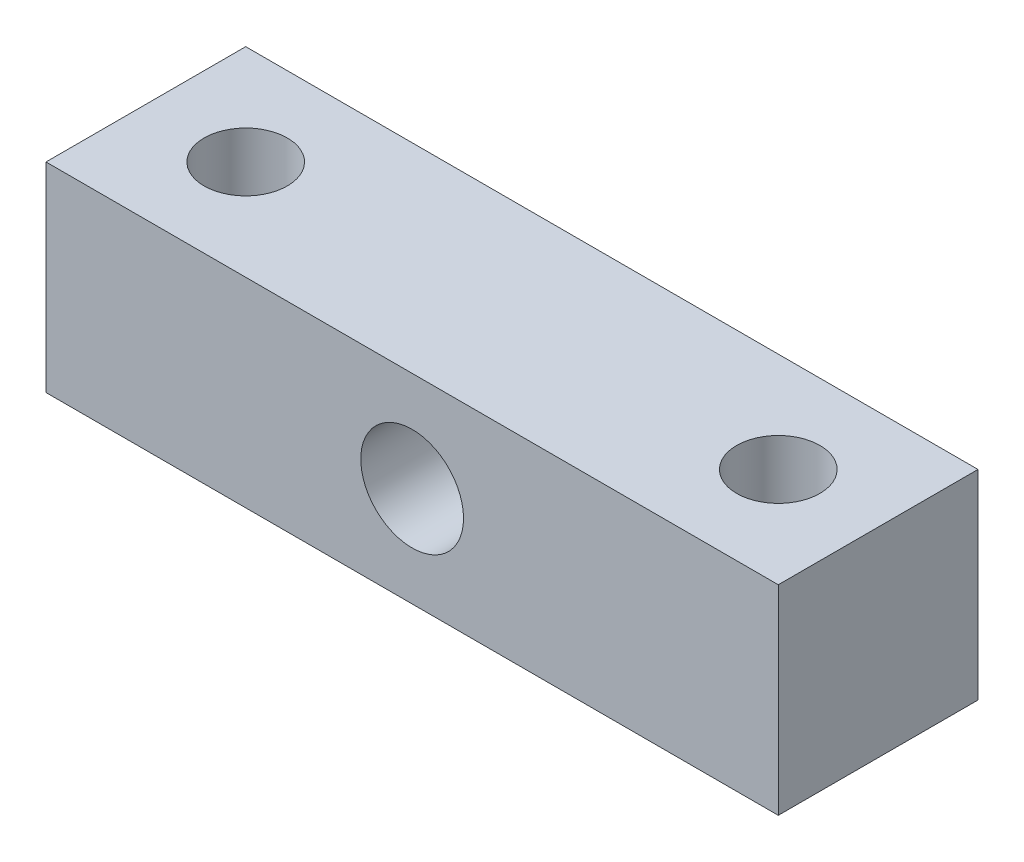
SolidWorks part; units mm, degrees
material "6061-T6 (SS)"
ref_plane "Front" through (0, 0, 0) normal (0, 0, 1) x (1, 0, 0)
ref_plane "Top" through (0, 0, 0) normal (0, 1, 0) x (1, 0, 0)
ref_plane "Right" through (0, 0, 0) normal (1, 0, 0) x (0, 0, -1)
sketch "Sketch1" plane through (0, 0, 0) normal (0, 0, 1) x (1, 0, 0)
  line L1 (-34.925, -9.525) -> (34.925, -9.525)
  line L2 (-34.925, -9.525) -> (-34.925, 9.525)
  line L3 (-34.925, 9.525) -> (34.925, 9.525)
  line L4 (34.925, -9.525) -> (34.925, 9.525)
  line L5 (-34.925, -9.525) -> (34.925, 9.525) construction
  line L6 (-34.925, 9.525) -> (34.925, -9.525) construction
  point P0 (0, 0)
  dimension "D1" = 69.85
  dimension "D2" = 19.05
extrude "Boss-Extrude1" add sketch "Sketch1" along normal blind 19.05
sketch "Sketch2" plane through (0, 0, 19.05) normal (0, 0, 1) x (1, 0, 0)
  line L0 (0, 9.525) -> (0, 0) construction
  line L1 (34.925, 9.525) -> (-34.925, 9.525) construction
  line L2 (0, 0) -> (0, -9.525) construction
  line L3 (-34.925, -9.525) -> (34.925, -9.525) construction
hole_wizard "3/8 Clearance Hole1" positions "Sketch4" profile "Sketch3" hole size "3/8" standard "ANSI Inch" end condition through all
sketch "Sketch4" plane through (0, 0, 19.05) normal (0, 0, 1) x (1, 0, 0)
  point P0 (0, 0)
sketch "Sketch3" plane through (0, 0, 19.05) normal (1, 0, 0) x (0, -1, 0)
  line L0 (0, 0) -> (0, 19.05)
  line L1 (0, 19.05) -> (4.9022, 19.05)
  line L2 (4.9022, 19.05) -> (4.9022, 0)
  line L5 (4.9022, 0) -> (0, 0)
  line L11 (0, -6.35) -> (0, 107.95) construction
  dimension "Thru Hole Dia." = 9.8044
  dimension "Thru Hole Depth" = 19.05
sketch "Sketch5" plane through (0, 9.525, 0) normal (0, 1, 0) x (1, 0, 0)
  line L0 (34.925, -9.525) -> (25.4, -9.525) construction
  line L1 (34.925, -19.05) -> (34.925, 0) construction
  line L2 (25.4, -9.525) -> (-25.4, -9.525) construction
  line L3 (-25.4, -9.525) -> (-34.925, -9.525) construction
  line L4 (-34.925, -19.05) -> (-34.925, 0) construction
  dimension "D1" = 50.8
hole_wizard "5/16 (0.3125) Diameter Hole1" positions "Sketch7" profile "Sketch6" hole size "5/16" standard "ANSI Inch" end condition through all
sketch "Sketch7" plane through (0, 9.525, 0) normal (0, 1, 0) x (1, 0, 0)
  point P0 (-25.4, -9.525)
  point P3 (25.4, -9.525)
sketch "Sketch6" plane through (-25.4, 9.525, 9.525) normal (1, 0, 0) x (0, 0, 1)
  line L0 (0, 0) -> (0, 19.05)
  line L1 (0, 19.05) -> (3.9687, 19.05)
  line L2 (3.9687, 19.05) -> (3.9687, 0)
  line L5 (3.9687, 0) -> (0, 0)
  line L11 (0, -6.35) -> (0, 107.95) construction
  dimension "Thru Hole Dia." = 7.9375
  dimension "Thru Hole Depth" = 19.05
